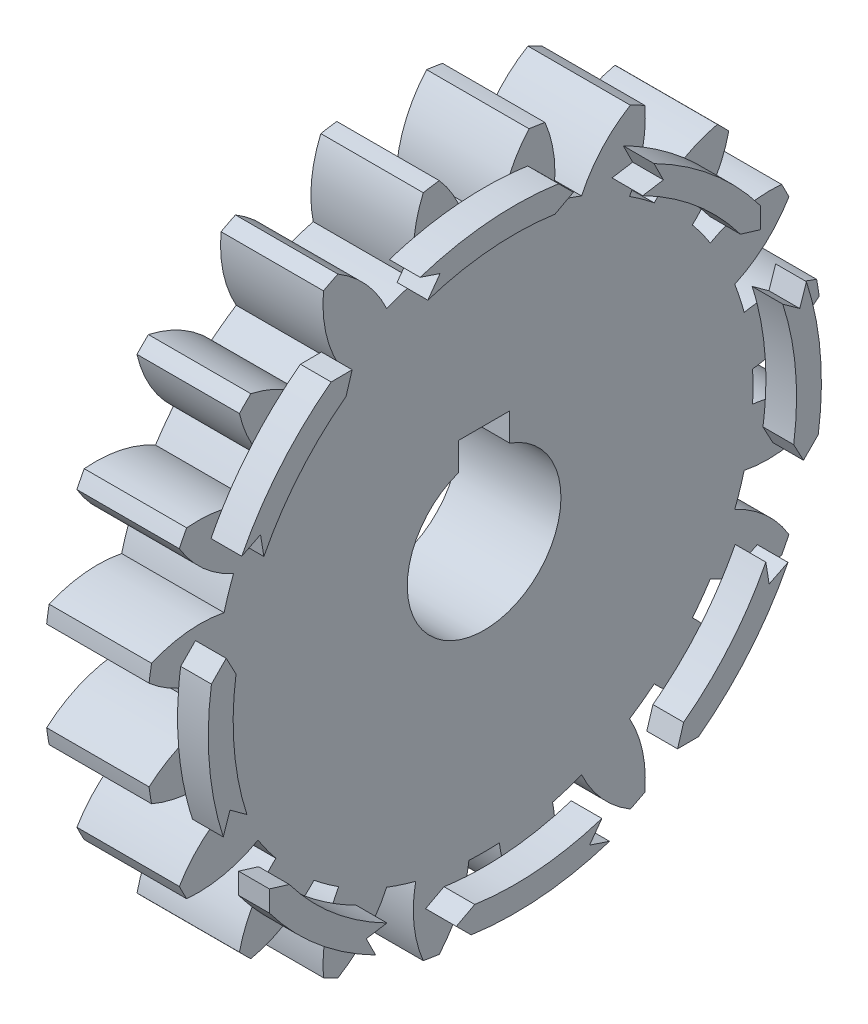
SolidWorks part; units mm, degrees
ref_plane "Plane1" through (0, 0, 0) normal (0, 0, 1) x (1, 0, 0)
ref_plane "Plane2" through (0, 0, 0) normal (0, 1, 0) x (1, 0, 0)
ref_plane "Plane3" through (0, 0, 0) normal (1, 0, 0) x (0, 0, -1)
sketch "HoldingSke" plane through (0, 0, 0) normal (0, 1, 0) x (1, 0, 0)
  line L0 (0, 0) -> (0.3132, -0.114)
  line L1 (-15, 0) -> (100, 0) construction
  line L2 (0, 0) -> (-2.1039, 2.3779)
  line L3 (0, 0) -> (-11.863, 4.5341)
  line L4 (0, 0) -> (8.1152, 2.9537)
  line L5 (0, 0) -> (-46.8476, -17.4728)
  line L6 (0, 0) -> (-8.2896, -5.593)
  line L7 (-2.1039, 2.3779) -> (8.6587, 51.2065)
  line L8 (-76.2, 54.61) -> (-73.9, 54.61)
  line L9 (-71.009, 38.7566) -> (-53.1078, 45.2721)
  line L10 (-76.2, 71.12) -> (104.1128, 71.12)
  line L11 (0, 0) -> (-10, 0)
  line L12 (-76.2, 101.6) -> (-76.093, 101.6)
  line L13 (24.9733, 27.94) -> (52.9518, 28.4284)
  line L14 (24.9733, 27.94) -> (24.9743, 27.94)
  line L15 (24.9733, 27.94) -> (100.4006, 29.5858)
  line L16 (-63.627, -3) -> (-12.827, -3)
  circle A0 centre (0, 0) radius 7.5
  circle A1 centre (0, 0) radius 24.0615
  circle A2 centre (0, 0) radius 37.5
  circle A3 centre (0, 0) radius 7.5
  dimension "MHD" = 48.123
  dimension "Hub_dia" = 75
  dimension "Bore" = 15
  dimension "MBD" = 15
  dimension "Num_teeth" = 20
  dimension "Pitch" = 0.3333
  dimension "Overall_len" = 50
  dimension "Show_teeth" = 20
  dimension "Thickness" = 10
  dimension "OAL" = 50.0007
  dimension "T_dim" = 2.3
  dimension "Ap" = 20
  dimension "H" = 19.05
  dimension "Pitch_radius" = 180.3128
  dimension "Width" = 10
  dimension "Backlash" = 0.107
  dimension "Addendum_fac" = 1
  dimension "Dedendum_fac" = 1.25
  dimension "Clearance_fac" = 0.25
  dimension "Dedendum_add" = 0.001
  dimension "Module" = 3
sketch "BasProSke" plane through (0, 0, 0) normal (0, 1, 0) x (1, 0, 0)
  line L0 (-10, 0) -> (60, 0) construction
  line L1 (0, 0) -> (0, 33)
  line L2 (0, 0) -> (10, 0)
  line L3 (10, 0) -> (10, 33)
  line L4 (10, 33) -> (0, 33)
  dimension "Thickness" = 10
  dimension "Diameter" = 66
revolve "Base-Revolve" add sketch "BasProSke" angle 360 about L0
sketch "TooCutSke" plane through (0, 0, 0) normal (1, 0, 0) x (0, 0, -1)
  line L1 (0, 0) -> (0, 107) construction
  line L2 (0, 0) -> (-2.5409, 29.8922) construction
  line L3 (0, 0) -> (-9.3616, 59.1066) construction
  line L4 (-2.5409, 29.8922) -> (-4.6808, 29.5533) construction
  arc A0 (1.4893, 26.2067) -> (-1.4893, 26.2067) centre (0, 0) ccw
  arc A1 (4.4016, 32.7308) -> (-4.4016, 32.7308) centre (0, 0) ccw
  circle A2 centre (0, 0) radius 30 construction
  circle A3 centre (0, 0) radius 28.1908 construction
  arc A4 (-1.4893, 26.2067) -> (-4.4016, 32.7308) centre (-13.4064, 24.799) ccw
  arc A5 (4.4016, 32.7308) -> (1.4893, 26.2067) centre (13.4064, 24.799) ccw
  dimension "Root_dia" = 52.498
  dimension "Overcut_dia" = 66.0508
  dimension "Pitch_dia" = 60
  dimension "Base_dia" = 56.3816
  dimension "Flank_rad" = 12
  dimension "Half_ang" = 9
  dimension "Half_CT" = 2.1665
extrude "ToothCut" cut sketch "TooCutSke" along normal through all
fillet "Breaks" [suppressed] radius 0.06
fillet "RootFillets" [suppressed] radius 0.751
pattern_circular "TeethCuts" count 20 every 18 about axis through (-10, 0, 0) along (1, 0, 0) of "ToothCut", "RootFillets", "Breaks"
sketch "HubNeaOneSke" plane through (0, 0, 0) normal (-1, 0, 0) x (0, 0, 1)
  circle A0 centre (0, 0) radius 24.0615
  dimension "Diameter" = 48.123
extrude "HubNearOne" [suppressed] add sketch "HubNeaOneSke" along normal blind 40.0007
sketch "HubNeaBotSke" plane through (0, 0, 0) normal (-1, 0, 0) x (0, 0, 1)
  circle A0 centre (0, 0) radius 24.0615
  dimension "Diameter" = 48.123
extrude "HubNearBoth" [suppressed] add sketch "HubNeaBotSke" along normal blind 20.0004
ref_plane "FarPln" through (10, 0, 0) normal (1, 0, 0) x (0, 0, -1)
sketch "HubFarSke" plane through (10, 0, 0) normal (1, 0, 0) x (0, 0, -1)
  circle A0 centre (0, 0) radius 24.0615
  dimension "Diameter" = 48.123
extrude "HubFar" [suppressed] add sketch "HubFarSke" along normal blind 20.0004
sketch "BorSke" plane through (0, 0, 0) normal (1, 0, 0) x (0, 0, -1)
  circle A0 centre (0, 0) radius 7.5
  dimension "Diameter" = 15
extrude "Bore" cut sketch "BorSke" along normal mid plane 100.0014
sketch "KeySke" plane through (0, 0, 0) normal (1, 0, 0) x (0, 0, -1)
  line L0 (-2.5, 0) -> (-2.5, 9.8)
  line L1 (-2.5, 9.8) -> (2.5, 9.8)
  line L2 (2.5, 9.8) -> (2.5, 0)
  line L3 (0, 0) -> (0, 34) construction
  line L4 (-2.5, 0) -> (2.5, 0)
  dimension "Offset" = 9.8
  dimension "Width" = 5
extrude "Keyway" cut sketch "KeySke" along normal mid plane 100.0014
pattern_circular "Keyway2" [suppressed] count 2 every 90 about axis through (-10, 0, 0) along (1, 0, 0)
sketch "Sketch1" plane through (10, 0, 0) normal (1, 0, 0) x (0, 0, -1)
  line L0 (0, 0) -> (-26.6618, 13.5887)
  line L1 (0, 0) -> (-25.8396, 15.0937)
  line L2 (-26.6618, 13.5887) -> (-24.8251, 14.501)
  line L3 (-24.8251, 14.501) -> (-24.5013, 12.4875)
  line L4 (0, 0) -> (-17.9318, 23.9574)
  line L5 (0, 0) -> (-16.53, 24.9453)
  line L6 (-17.9318, 23.9574) -> (-15.8809, 23.9658)
  line L7 (-15.8809, 23.9658) -> (-16.4786, 22.016)
  circle A0 centre (0, 0) radius 29.925
  circle A1 centre (0, 0) radius 27.5
  circle A2 centre (0, 0) radius 28.75
  dimension "D1" = 59.85
  dimension "D2" = 55
  dimension "D3" = 57.5
extrude "Boss-Extrude1" add sketch "Sketch1" along normal blind 3 contours A2 L4 A0 L1 | L1 A0 L2 | A1 L1 L3 | L4 A2 L1 A1 | A2 L6 L4 | L7 A2 L4
pattern_circular "CirPattern1" count 8 over 360 about axis through (0, 0, 0) along (1, 0, 0) of "Boss-Extrude1"
equation "' \"Module@HoldingSke\" = 6.35"
equation "' \"Num_teeth@HoldingSke\" = 12"
equation "' \"Ap@HoldingSke\" =  20"
equation "' \"Ap@HoldingSke\" = 20"
equation "' \"Width@HoldingSke\" = 0.5 * 25.4"
equation "' \"Hub_dia@HoldingSke\"= 1 * 25.4"
equation "' \"Hub_dia@HoldingSke\" = 1 * 25.4"
equation "' \"Overall_len@HoldingSke\" = 1.0 * 25.4"
equation "' \"Bore@HoldingSke\" = 0.75 * 25.4"
equation "' \"T_dim@HoldingSke\" = 0.1 * 25.4"
equation "' \"Width@KeySke\" = 0.25 * 25.4"
equation "' \"Show_teeth@HoldingSke\" = 13"
equation "' \"Backlash@HoldingSke\" = 0.009 * 25.4"
equation "' \"Addendum_fac@HoldingSke\" = 1.0"
equation "' \"Dedendum_fac@HoldingSke\" = 1.25"
equation "' \"Dedendum_add@HoldingSke\" = 0.00005 * 25.4"
equation "' \"Clearance_fac@HoldingSke\" = 0.25"
equation "\"Pitch@HoldingSke\" = 1 / \"Module@HoldingSke\""
equation "\"Overcut_dia@TooCutSke\" = (\"Num_teeth@HoldingSke\" + 2 * \"Addendum_fac@HoldingSke\") / \"Pitch@HoldingSke\" + 0.002 * 25.4"
equation "\"Pitch_dia@TooCutSke\" = \"Num_teeth@HoldingSke\" / \"Pitch@HoldingSke\""
equation "\"Base_dia@TooCutSke\" = \"Num_teeth@HoldingSke\" / \"Pitch@HoldingSke\" * cos((\"Ap@HoldingSke\"  * 3.14159265 / 180))"
equation "\"Root_dia@TooCutSke\" = (\"Num_teeth@HoldingSke\" + 2) / \"Pitch@HoldingSke\" - 2 * (\"Addendum_fac@HoldingSke\" + \"Dedendum_fac@HoldingSke\") / \"Pitch@HoldingSke\" - \"Dedendum_add@HoldingSke\" * 2"
equation "\"Half_ang@TooCutSke\" = 180 / \"Num_teeth@HoldingSke\""
equation "\"Half_CT@TooCutSke\" = \"Num_teeth@HoldingSke\" / \"Pitch@HoldingSke\" * sin((3.14159265 / 2 / \"Num_teeth@HoldingSke\")) / 2 - 7 * \"Backlash@HoldingSke\" / 4"
equation "\"Flank_rad@TooCutSke\" = \"Num_teeth@HoldingSke\" / \"Pitch@HoldingSke\" / 5"
equation "\"Radius@RootFillets\" = \"Clearance_fac@HoldingSke\" / \"Pitch@HoldingSke\" + \"Dedendum_add@HoldingSke\""
equation "\"Break_rad@Breaks\" = 0.02 / \"Pitch@HoldingSke\""
equation "\"Thickness@HoldingSke\" = \"Width@HoldingSke\""
equation "\"OAL@HoldingSke\" = \"Thickness@HoldingSke\""
equation "\"MHD@HoldingSke\" = (\"Num_teeth@HoldingSke\" + 2) / \"Pitch@HoldingSke\" - 2 * (\"Addendum_fac@HoldingSke\" + \"Dedendum_fac@HoldingSke\")  / \"Pitch@HoldingSke\" - \"Dedendum_add@HoldingSke\" * 2"
equation "\"MBD@HoldingSke\" = (\"Num_teeth@HoldingSke\" + 2) / \"Pitch@HoldingSke\" - 2 * (\"Addendum_fac@HoldingSke\" + \"Dedendum_fac@HoldingSke\")  / \"Pitch@HoldingSke\" - \"Dedendum_add@HoldingSke\" * 2 - 0.002 * 25.4"
equation "\"MHD@HoldingSke\" = ((sgn( \"MHD@HoldingSke\" - \"Hub_dia@HoldingSke\" )-1)*( \"MHD@HoldingSke\" - \"Hub_dia@HoldingSke\" ))/-2+ \"Hub_dia@HoldingSke\""
equation "\"MBD@HoldingSke\" = ((sgn( \"MBD@HoldingSke\" - \"Bore@HoldingSke\" )-1)*( \"MBD@HoldingSke\" - \"Bore@HoldingSke\" ))/-2+ \"Bore@HoldingSke\""
equation "\"OAL@HoldingSke\" = ((sgn( \"OAL@HoldingSke\" - \"Overall_len@HoldingSke\" )+1)*( \"OAL@HoldingSke\" - \"Overall_len@HoldingSke\" ))/2 + \"Overall_len@HoldingSke\" + 0.000002 * 25.4"
equation "\"Num_teeth@TeethCuts\" = int( \"Show_teeth@HoldingSke\" ) + 1"
equation "\"Num_teeth@TeethCuts\" = ((sgn( \"Num_teeth@TeethCuts\" - \"Num_teeth@HoldingSke\" )-1)*( \"Num_teeth@TeethCuts\" - \"Num_teeth@HoldingSke\" ))/-2+ \"Num_teeth@HoldingSke\""
equation "\"Num_teeth@TeethCuts\" = ((sgn( \"Num_teeth@TeethCuts\" - 2.0)+1)*( \"Num_teeth@TeethCuts\" - 2.0))/2 +2.0"
equation "\"Angle@TeethCuts\" = 360.0 / \"Num_teeth@HoldingSke\""
equation "\"Diameter@BasProSke\" = (\"Num_teeth@HoldingSke\" + 2 * \"Addendum_fac@HoldingSke\") / \"Pitch@HoldingSke\""
equation "\"Thickness@BasProSke\"  = \"Thickness@HoldingSke\""
equation "' \"Fillet_rad@BasProSke\" =  \"Thickness@HoldingSke\" * 0.05"
equation "' \"Fillet_rad@BasProSke\" = \"Thickness@HoldingSke\" * 0.05"
equation "\"MHD@HoldingSke\"= ( ( sgn ( \"MHD@HoldingSke\" - \"Root_dia@TooCutSke\" ) - 1 ) * ( \"MHD@HoldingSke\" - \"Root_dia@TooCutSke\" ) ) / - 2 + \"Root_dia@TooCutSke\""
equation "\"Diameter@HubNeaOneSke\" = \"MHD@HoldingSke\""
equation "\"Length@HubNearOne\" = \"OAL@HoldingSke\" - \"Thickness@BasProSke\""
equation "\"Diameter@HubNeaBotSke\" = \"MHD@HoldingSke\""
equation "\"Length@HubNearBoth\" = ( \"OAL@HoldingSke\" - \"Thickness@BasProSke\" ) / 2.0"
equation "\"Thickness@FarPln\" = \"Thickness@BasProSke\""
equation "\"Diameter@HubFarSke\" = \"MHD@HoldingSke\""
equation "\"Length@HubFar\" = ( \"OAL@HoldingSke\" - \"Thickness@BasProSke\" ) / 2.0"
equation "\"Diameter@BorSke\" = \"MBD@HoldingSke\""
equation "\"D1@Bore\" = \"OAL@HoldingSke\" * 2.0"
equation "\"D1@Keyway\" = \"OAL@HoldingSke\" * 2.0"
equation "\"Offset@KeySke\" = \"T_dim@HoldingSke\" + \"MBD@HoldingSke\" / 2.0"
